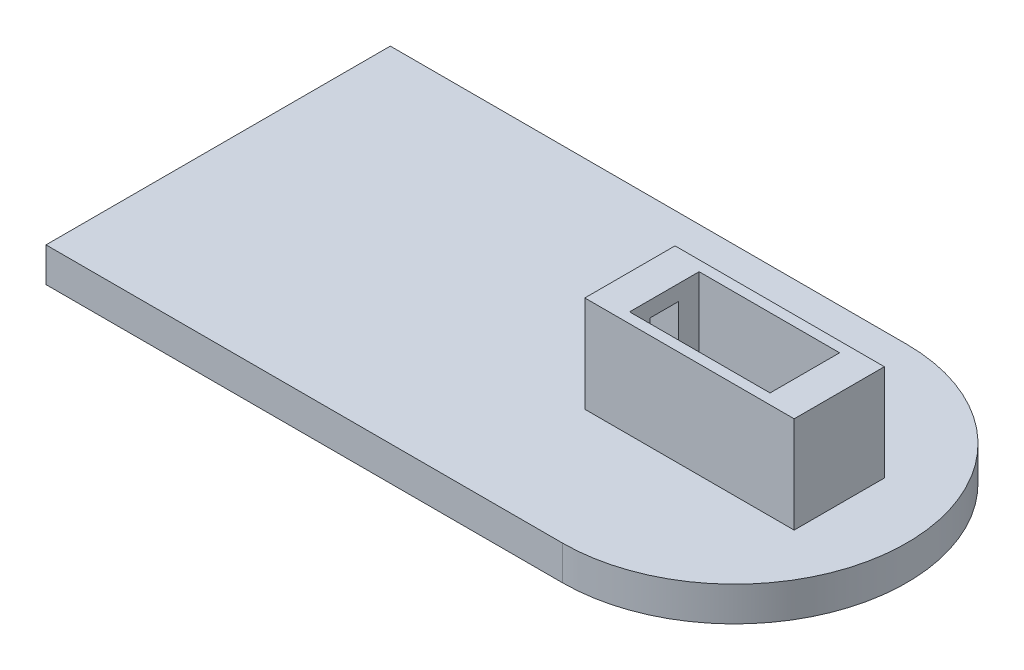
SolidWorks part; units mm, degrees
ref_plane "Front Plane" through (0, 0, 0) normal (0, 0, 1) x (1, 0, 0)
ref_plane "Top Plane" through (0, 0, 0) normal (0, 1, 0) x (1, 0, 0)
ref_plane "Right Plane" through (0, 0, 0) normal (1, 0, 0) x (0, 0, -1)
sketch "Sketch2" plane through (0, 0, 0) normal (0, 1, 0) x (1, 0, 0)
  line L1 (-75, 50) -> (75, 50)
  line L2 (-75, 50) -> (-75, -50)
  line L3 (-75, -50) -> (75, -50)
  line L5 (-75, 50) -> (75, -50) construction
  line L6 (-75, -50) -> (75, 50) construction
  arc A0 (75, -50) -> (75, 50) centre (75, 0) ccw
  point P0 (0, 0)
  point P8 (75, 0)
  point P9 (75, 0)
  dimension "D3" = 50
  dimension "D1" = 150
  dimension "D2" = 100
extrude "Boss-Extrude4" add sketch "Sketch2" along normal blind 10 contours L1 A0 L3 L2
sketch "Sketch5" plane through (0, 10, 0) normal (0, 1, 0) x (1, 0, 0)
sketch "Sketch6" plane through (0, 10, 0) normal (0, 1, 0) x (1, 0, 0)
  line L0 (51.6, 13.1) -> (98.4, 13.1)
  line L1 (54.6, 10.1) -> (95.4, 10.1)
  line L2 (54.6, 10.1) -> (54.6, -10.1)
  line L3 (54.6, -10.1) -> (95.4, -10.1)
  line L4 (95.4, 10.1) -> (95.4, -10.1)
  line L5 (54.6, 10.1) -> (95.4, -10.1) construction
  line L6 (54.6, -10.1) -> (95.4, 10.1) construction
  line L7 (98.4, 13.1) -> (98.4, -13.1)
  line L8 (51.6, -13.1) -> (98.4, -13.1)
  line L9 (51.6, 13.1) -> (51.6, -13.1)
  point P0 (75, 0)
  dimension "D1" = 40.8
  dimension "D2" = 20.2
  dimension "D3" = 3
extrude "Boss-Extrude5" add sketch "Sketch6" along normal blind 28 contours L0 L7 L8 L9 | L2 L1 L4 L3
sketch "Sketch8" plane through (51.6, 0, 0) normal (-1, 0, 0) x (0, 0, 1)
  line L0 (-4.175, 33.5) -> (4.175, 33.5)
  line L1 (-4.175, 33.5) -> (-4.175, 13.5)
  line L2 (-4.175, 13.5) -> (4.175, 13.5)
  line L3 (4.175, 33.5) -> (4.175, 13.5)
  line L4 (-4.175, 33.5) -> (4.175, 13.5) construction
  line L5 (-4.175, 13.5) -> (4.175, 33.5) construction
  line L7 (13.1, 38) -> (13.1, 10) construction
  line L8 (-13.1, 10) -> (13.1, 10) construction
  point P0 (0, 23.5)
  dimension "D1" = 8.35
  dimension "D2" = 20
  dimension "D3" = 8.925
  dimension "D4" = 3.5
extrude "Cut-Extrude2" cut sketch "Sketch8" against normal blind 28
sketch "Sketch12" plane through (98.4, 0, 0) normal (1, 0, 0) x (0, 0, -1)
  line L1 (-13.1, 38) -> (13.1, 38)
  line L2 (-13.1, 38) -> (-13.1, 10)
  line L3 (-13.1, 10) -> (13.1, 10)
  line L4 (13.1, 38) -> (13.1, 10)
extrude "Boss-Extrude6" add sketch "Sketch12" along normal blind 7
sketch "Sketch13" plane through (51.6, 0, 0) normal (-1, 0, 0) x (0, 0, 1)
  line L0 (-13.1, 10) -> (13.1, 10) construction
  line L1 (4.175, 13.5) -> (-4.175, 13.5)
  line L2 (4.175, 13.5) -> (4.175, 10)
  line L3 (4.175, 10) -> (-4.175, 10)
  line L4 (-4.175, 13.5) -> (-4.175, 10)
  line L5 (-13.1, 38) -> (13.1, 38) construction
  line L6 (-4.175, 33.5) -> (4.175, 33.5)
  line L7 (-4.175, 33.5) -> (-4.175, 38)
  line L8 (-4.175, 38) -> (4.175, 38)
  line L9 (4.175, 33.5) -> (4.175, 38)
  line L11 (13.1, 38) -> (4.175, 38)
  line L12 (13.1, 38) -> (13.1, 10)
  line L13 (13.1, 10) -> (4.175, 10)
  line L14 (4.175, 38) -> (4.175, 10)
  line L15 (-13.1, 38) -> (-4.175, 38)
  line L16 (-13.1, 38) -> (-13.1, 10)
  line L17 (-13.1, 10) -> (-4.175, 10)
  line L18 (-4.175, 38) -> (-4.175, 10)
  line M17 (-4.175, 33.5) -> (4.175, 33.5)
  line M18 (4.175, 33.5) -> (4.175, 13.5)
  line M19 (4.175, 13.5) -> (-4.175, 13.5)
  line M20 (-4.175, 13.5) -> (-4.175, 33.5)
  line M21 (-13.1, 10) -> (13.1, 10)
  line M22 (13.1, 10) -> (13.1, 38)
  line M23 (13.1, 38) -> (-13.1, 38)
  line M24 (-13.1, 38) -> (-13.1, 10)
extrude "Boss-Extrude7" add sketch "Sketch13" along normal blind 7 contours L7 L4 M20 M23 M24 M21 | L9 L7 M17 M23 | L9 L2 M18 M21 M22 M23 | L4 L2 M19 M21
